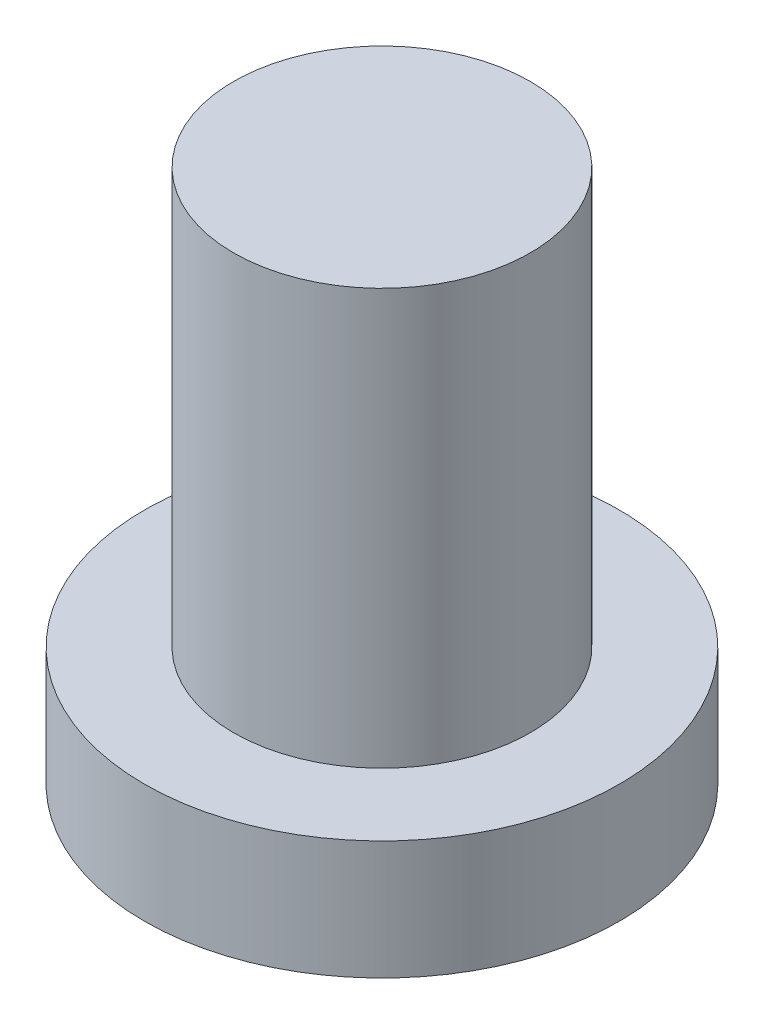
SolidWorks part; units mm, degrees
ref_plane "Plan1" through (0, 0, 0) normal (0, 0, 1) x (1, 0, 0)
ref_plane "Plan2" through (0, 0, 0) normal (0, 1, 0) x (1, 0, 0)
ref_plane "Plan3" through (0, 0, 0) normal (1, 0, 0) x (0, 0, -1)
ref_plane "Plan4" through (0, 0, 742.5) normal (0, 0, -1) x (-1, 0, 0)
sketch "Esquisse1" plane through (0, 0, 742.5) normal (0, 0, -1) x (-1, 0, 0)
  line L0 (-2140, 625.5) -> (-2136, 625.5)
  line L1 (-2136, 625.5) -> (-2136, 634.5)
  line L2 (-2136, 634.5) -> (-2138.5, 634.5)
  line L3 (-2138.5, 634.5) -> (-2138.5, 627.5)
  line L4 (-2138.5, 627.5) -> (-2140, 627.5)
  line L5 (-2140, 627.5) -> (-2140, 625.5)
  line L6 (-2136, 625.5) -> (-2136, 634.5) construction
  dimension "D1" = 9
  dimension "D2" = 2
  dimension "D3" = 5
  dimension "D4" = 8
revolve "Base-Révolution" add sketch "Esquisse1" angle 360 about L6
